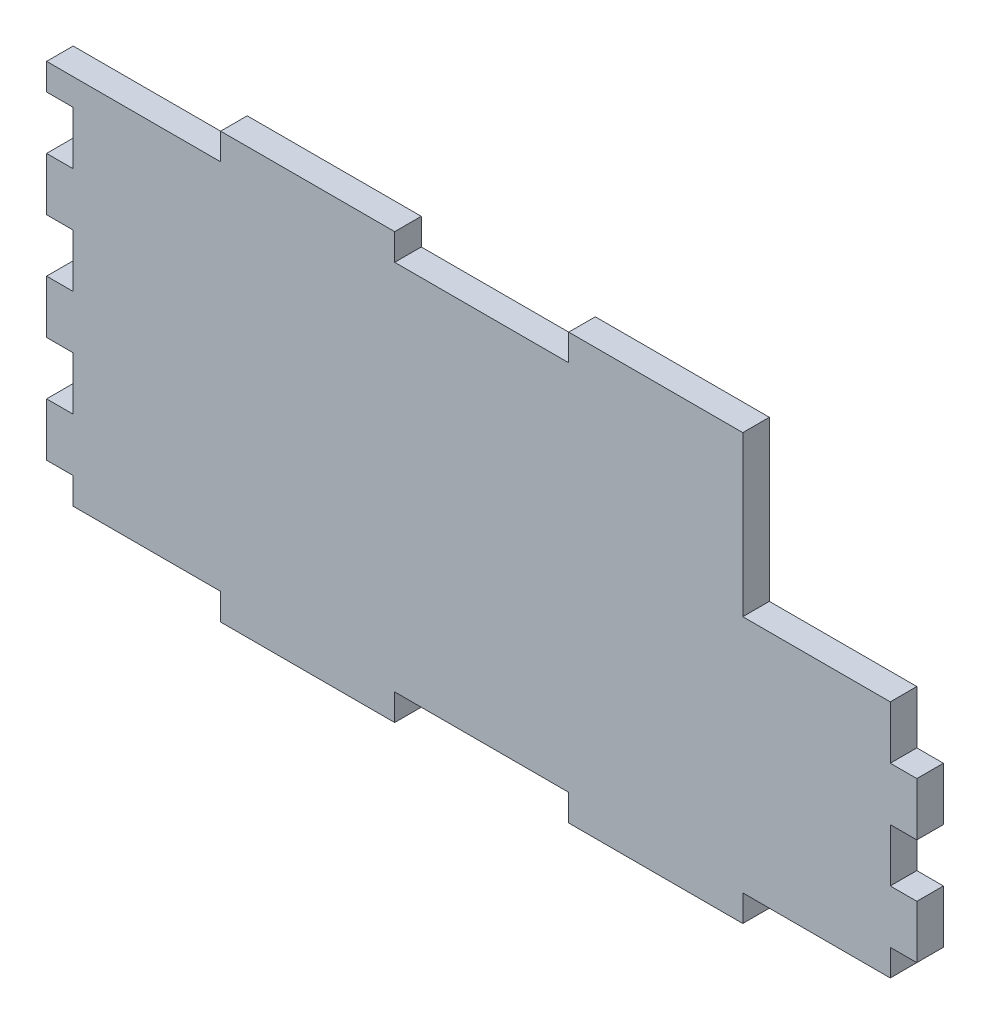
SolidWorks part; units mm, degrees
ref_plane "Front Plane" through (0, 0, 0) normal (0, 0, 1) x (1, 0, 0)
ref_plane "Top Plane" through (0, 0, 0) normal (0, 1, 0) x (1, 0, 0)
ref_plane "Right Plane" through (0, 0, 0) normal (1, 0, 0) x (0, 0, -1)
sketch "Sketch1" plane through (0, 0, 0) normal (0, 0, 1) x (1, 0, 0)
  line L1 (-103.9812, -50.8) -> (103.9813, -50.8)
  line L2 (-103.9812, -50.8) -> (-103.9812, 50.8)
  line L3 (-103.9812, 50.8) -> (103.9813, 50.8)
  line L4 (103.9813, -50.8) -> (103.9813, 50.8)
  line L5 (-103.9812, -50.8) -> (103.9813, 50.8) construction
  line L6 (-103.9812, 50.8) -> (103.9813, -50.8) construction
  point P0 (0, 0)
  dimension "D1" = 207.9625
  dimension "D2" = 101.6
extrude "Boss-Extrude1" add sketch "Sketch1" along normal blind 6.35
sketch "Sketch2" plane through (0, 0, 6.35) normal (0, 0, 1) x (1, 0, 0)
  line L0 (-20.7962, 50.8) -> (-20.7962, 44.45)
  line L1 (-103.9812, 50.8) -> (-62.3887, 50.8)
  line L2 (-103.9812, 50.8) -> (-103.9812, 44.45)
  line L3 (-103.9812, 44.45) -> (-62.3887, 44.45)
  line L4 (-62.3887, 50.8) -> (-62.3887, 44.45)
  line L5 (-20.7962, 50.8) -> (20.7963, 50.8)
  line L6 (20.7963, 50.8) -> (20.7963, 44.45)
  line L7 (-20.7962, 44.45) -> (20.7963, 44.45)
  line L8 (62.3888, 50.8) -> (62.3888, 44.45)
  line L9 (62.3888, 50.8) -> (103.9813, 50.8)
  line L10 (103.9813, 50.8) -> (103.9813, 44.45)
  line L11 (62.3888, 44.45) -> (103.9813, 44.45)
  line L12 (0, 0) -> (17.3183, 0)
  line L13 (62.3888, -50.8) -> (103.9813, -50.8)
  line L14 (103.9813, -50.8) -> (103.9813, -44.45)
  line L15 (62.3888, -44.45) -> (103.9813, -44.45)
  line L16 (62.3888, -50.8) -> (62.3888, -44.45)
  line L17 (-20.7962, -50.8) -> (20.7963, -50.8)
  line L18 (20.7963, -50.8) -> (20.7963, -44.45)
  line L19 (-20.7962, -44.45) -> (20.7963, -44.45)
  line L20 (-20.7962, -50.8) -> (-20.7962, -44.45)
  line L21 (-103.9812, -44.45) -> (-62.3887, -44.45)
  line L22 (-62.3887, -50.8) -> (-62.3887, -44.45)
  line L23 (-103.9812, -50.8) -> (-62.3887, -50.8)
  line L24 (-103.9812, -50.8) -> (-103.9812, -44.45)
  line L25 (-103.9812, 50.8) -> (-103.9812, -50.8) construction
  line L26 (-103.9812, 38.1) -> (-97.6312, 38.1)
  line L27 (-103.9812, 38.1) -> (-103.9812, 25.4)
  line L28 (-103.9812, 25.4) -> (-97.6312, 25.4)
  line L29 (-97.6312, 38.1) -> (-97.6312, 25.4)
  line L30 (-103.9812, 12.7) -> (-103.9812, 0)
  line L31 (-103.9812, 12.7) -> (-97.6312, 12.7)
  line L32 (-97.6312, 12.7) -> (-97.6312, 0)
  line L33 (-103.9812, 0) -> (-97.6312, 0)
  line L34 (-103.9812, -12.7) -> (-103.9812, -25.4)
  line L35 (-103.9812, -12.7) -> (-97.6312, -12.7)
  line L36 (-97.6312, -12.7) -> (-97.6312, -25.4)
  line L37 (-103.9812, -25.4) -> (-97.6312, -25.4)
  line L38 (-103.9812, -38.1) -> (-103.9812, -50.8)
  line L39 (-103.9812, -38.1) -> (-97.6312, -38.1)
  line L40 (-97.6312, -38.1) -> (-97.6312, -50.8)
  line L41 (-103.9812, -50.8) -> (-97.6312, -50.8)
  line L42 (0, 0) -> (0, 23.1822)
  line L43 (103.9812, -38.1) -> (97.6312, -38.1)
  line L44 (97.6312, -38.1) -> (97.6312, -50.8)
  line L45 (103.9813, -50.8) -> (97.6312, -50.8)
  line L46 (103.9812, -38.1) -> (103.9813, -50.8)
  line L47 (103.9812, -12.7) -> (97.6312, -12.7)
  line L48 (97.6312, -12.7) -> (97.6312, -25.4)
  line L49 (103.9812, -25.4) -> (97.6312, -25.4)
  line L50 (103.9812, -12.7) -> (103.9812, -25.4)
  line L51 (103.9812, 12.7) -> (97.6312, 12.7)
  line L52 (97.6312, 12.7) -> (97.6312, 0)
  line L53 (103.9812, 0) -> (97.6312, 0)
  line L54 (103.9812, 12.7) -> (103.9812, 0)
  line L55 (103.9812, 25.4) -> (97.6312, 25.4)
  line L56 (97.6312, 38.1) -> (97.6312, 25.4)
  line L57 (103.9812, 38.1) -> (97.6312, 38.1)
  line L58 (103.9812, 38.1) -> (103.9812, 25.4)
  line M35 (103.9813, -50.8) -> (103.9813, 50.8)
  line M36 (103.9813, 50.8) -> (-103.9812, 50.8)
  line M37 (-103.9812, 50.8) -> (-103.9812, -50.8)
  line M38 (-103.9812, -50.8) -> (103.9813, -50.8)
  dimension "D1" = 41.5925
  dimension "D2" = 6.35
  dimension "D4" = 6.35
  dimension "D5" = 12.7
  dimension "D6" = 12.7
  dimension "D3" = 3
  dimension "D7" = 4
extrude "Cut-Extrude1" cut sketch "Sketch2" against normal blind 6.35 contours L4 L3 M36 M37 | L0 L7 L6 M36 | L8 L11 M35 M36 | L57 L56 L55 M35 | L53 L51 L52 M35 | L49 L47 L48 M35 | L43 L44 L15 M35 | L44 L15 L16 M38 | L15 L44 L13 M35 | L20 L18 L19 M38 | L40 L39 L21 M37 | L37 L36 L35 M37 | L33 L32 L31 M37 | L29 L26 L28 M37
sketch "Sketch3" plane through (0, 0, 6.35) normal (0, 0, 1) x (1, 0, 0)
  line L1 (62.3888, 44.45) -> (103.9813, 44.45)
  line L2 (62.3888, 44.45) -> (62.3888, 12.7)
  line L3 (62.3888, 12.7) -> (103.9813, 12.7)
  line L4 (103.9813, 44.45) -> (103.9813, 12.7)
extrude "Cut-Extrude2" cut sketch "Sketch3" against normal blind 6.35
